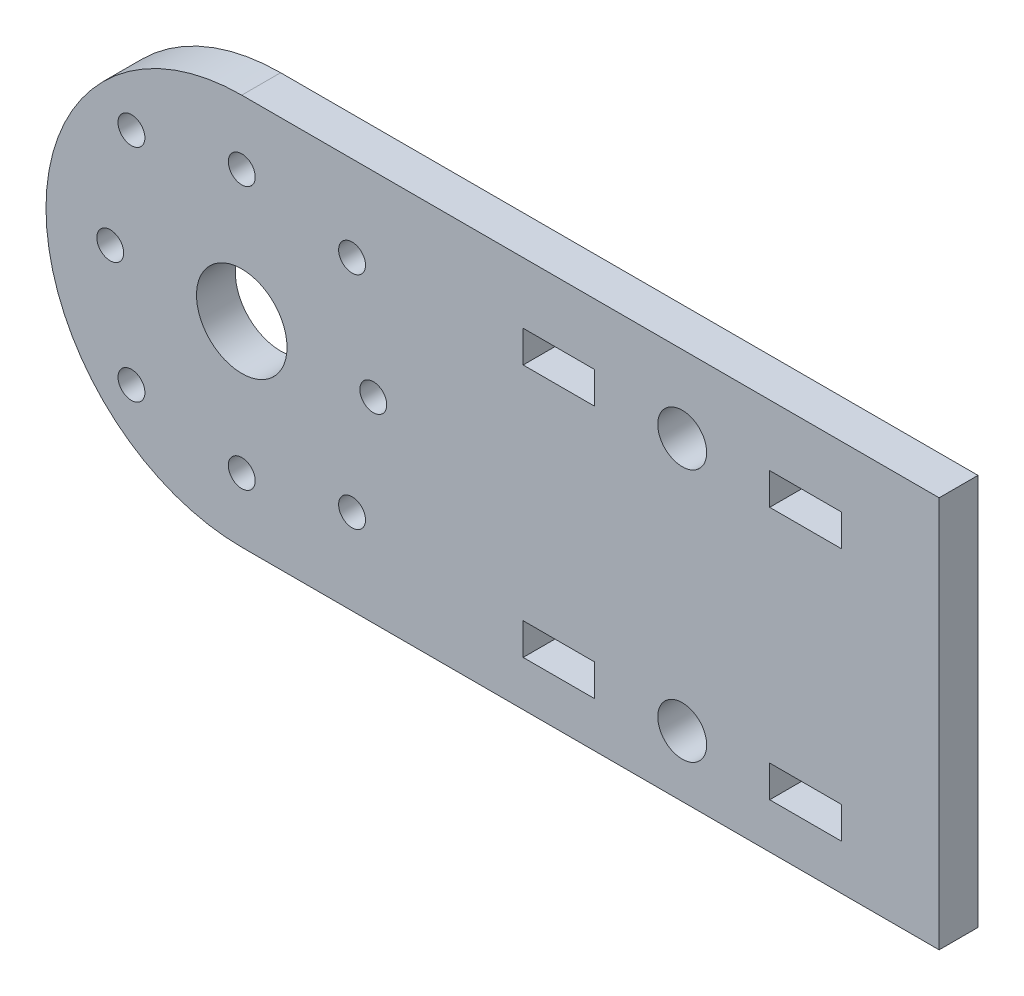
SolidWorks part; units mm, degrees
ref_plane "Front Plane" through (0, 0, 0) normal (0, 0, 1) x (1, 0, 0)
ref_plane "Top Plane" through (0, 0, 0) normal (0, 1, 0) x (1, 0, 0)
ref_plane "Right Plane" through (0, 0, 0) normal (1, 0, 0) x (0, 0, -1)
sketch "Sketch1" plane through (0, 0, 0) normal (0, 0, 1) x (1, 0, 0)
  line L1 (19, 0) -> (76, 0)
  line L2 (42, 27) -> (47.85, 27)
  line L3 (19, 32) -> (76, 32)
  line L4 (76, 0) -> (76, 32)
  line L5 (42, 27) -> (42, 24.4)
  line L6 (42, 24.4) -> (47.85, 24.4)
  line L7 (47.85, 27) -> (47.85, 24.4)
  line L8 (62.15, 27) -> (68, 27)
  line L9 (62.15, 27) -> (62.15, 24.4)
  line L10 (62.15, 24.4) -> (68, 24.4)
  line L11 (68, 27) -> (68, 24.4)
  line L12 (47.85, 6.3) -> (42, 6.3)
  line L13 (47.85, 6.3) -> (47.85, 3.7)
  line L14 (47.85, 3.7) -> (42, 3.7)
  line L15 (42, 6.3) -> (42, 3.7)
  line L16 (62.15, 6.3) -> (68, 6.3)
  line L17 (62.15, 6.3) -> (62.15, 3.7)
  line L18 (62.15, 3.7) -> (68, 3.7)
  line L19 (68, 6.3) -> (68, 3.7)
  arc A0 (19, 32) -> (19, 0) centre (19, 16) ccw
  circle A1 centre (8.25, 16) radius 1.1
  circle A2 centre (9.9844, 25.0156) radius 1.1
  circle A3 centre (28.0156, 25.0156) radius 1.1
  circle A4 centre (28.0156, 6.9844) radius 1.1
  circle A5 centre (9.9844, 6.9844) radius 1.1
  circle A6 centre (19, 26.75) radius 1.1
  circle A7 centre (29.75, 16) radius 1.1
  circle A8 centre (19, 5.25) radius 1.1
  circle A9 centre (19, 16) radius 3.7
  circle A10 centre (55, 5) radius 2
  circle A18 centre (55, 25.7) radius 2
  point P17 (19, 16)
  point P22 (19, 16)
  point P25 (19, 16)
  point P26 (19, 16)
  dimension "D3" = 19
  dimension "D6" = 12.75
  dimension "D7" = 2.2
  dimension "D8" = 45
  dimension "D10" = 5
  dimension "D22" = 1.3
  dimension "D23" = 4
  dimension "D4" = 2.2
  dimension "D5" = 10.75
  dimension "D9" = 7.4
  dimension "D11" = 4
  dimension "D1" = 32
  dimension "D12" = 2.6
  dimension "D13" = 1.3
  dimension "D14" = 5.85
  dimension "D15" = 5.85
  dimension "D16" = 26
  dimension "D17" = 2.6
  dimension "D18" = 2.6
  dimension "D19" = 8
  dimension "D20" = 5
  dimension "D21" = 13
  dimension "D24" = 76
extrude "Boss-Extrude1" add sketch "Sketch1" along normal blind 3.175
